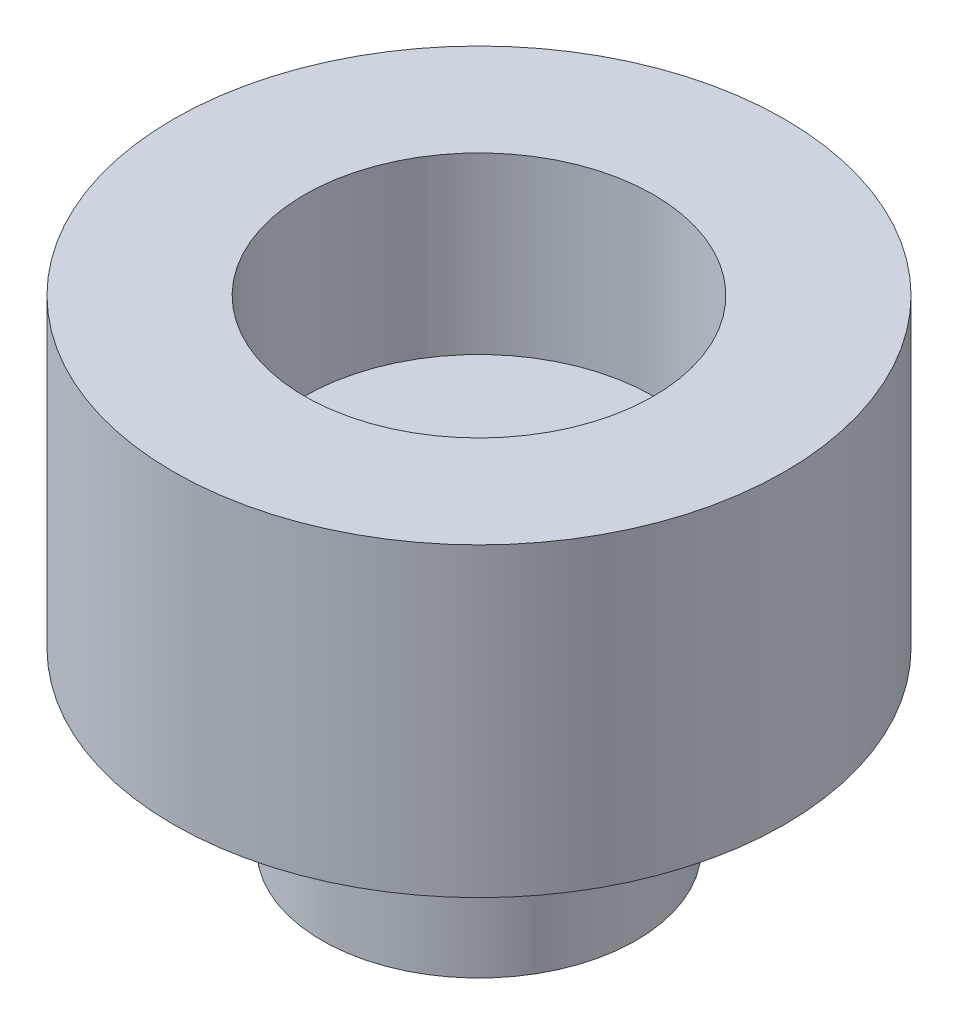
SolidWorks part; units mm, degrees
ref_plane "Plan de face" through (0, 0, 0) normal (0, 0, 1) x (1, 0, 0)
ref_plane "Plan de dessus" through (0, 0, 0) normal (0, 1, 0) x (1, 0, 0)
ref_plane "Plan de droite" through (0, 0, 0) normal (1, 0, 0) x (0, 0, -1)
sketch "Esquisse1" plane through (0, 0, 0) normal (0, 0, 1) x (1, 0, 0)
  line L0 (0, 0) -> (0, 3.5)
  line L1 (0, 3.5) -> (2, 3.5)
  line L2 (2, 3.5) -> (2, 5.5)
  line L3 (2, 5.5) -> (3.5, 5.5)
  line L4 (3.5, 5.5) -> (3.5, 2)
  line L7 (3.5, 2) -> (1.8, 2)
  line L8 (1.8, 2) -> (1.8, 0)
  line L9 (1.8, 0) -> (0, 0)
  point P3 (0, 0)
  dimension "D1" = 1.8
  dimension "D2" = 2
  dimension "D3" = 2
  dimension "D4" = 2
  dimension "D5" = 1.5
  dimension "D6" = 1.5
revolve "Révolution1" add sketch "Esquisse1" angle 360 about L0
